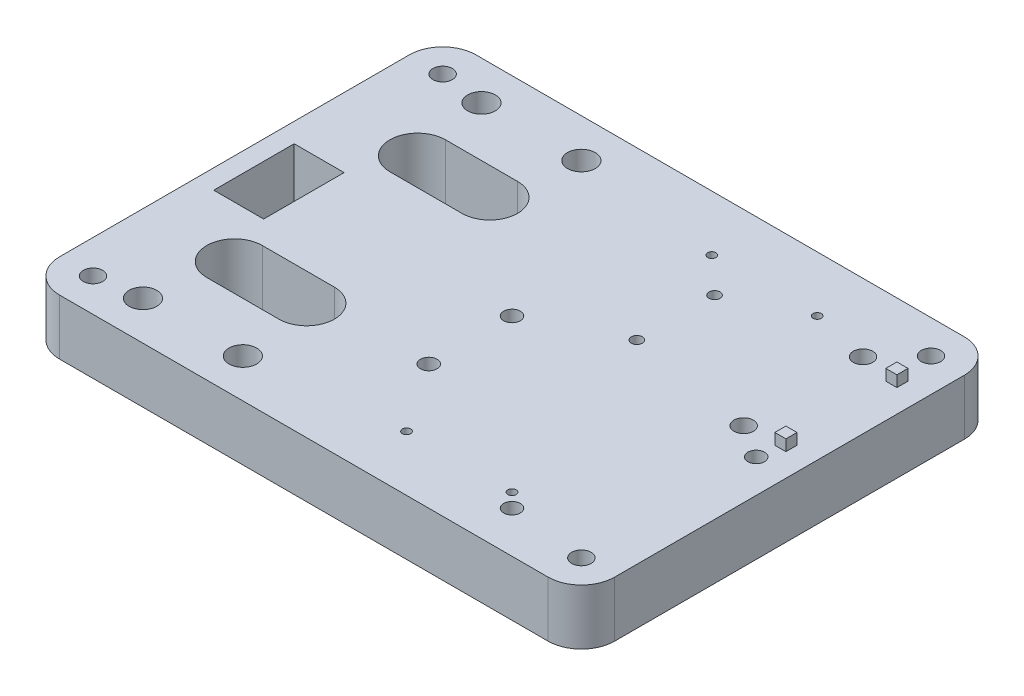
SolidWorks part; units mm, degrees
ref_plane "Спереди" through (0, 0, 0) normal (0, 0, 1) x (1, 0, 0)
ref_plane "Сверху" through (0, 0, 0) normal (0, 1, 0) x (1, 0, 0)
ref_plane "Справа" through (0, 0, 0) normal (1, 0, 0) x (0, 0, -1)
sketch "Эскиз1" plane through (0, 0, 0) normal (0, 1, 0) x (1, 0, 0)
  line L0 (0, 37.5) -> (100, 37.5) construction
  line L17 (0, 0) -> (100, 0)
  line L18 (0, 0) -> (0, 75)
  line L19 (0, 75) -> (100, 75)
  line L20 (100, 0) -> (100, 75)
  line L21 (50, 75) -> (50, 0) construction
  line L22 (23, 75) -> (23, 0) construction
  line L25 (16.5, 54) -> (29.5, 54) construction
  line L26 (16.5, 59) -> (29.5, 59)
  line L27 (16.5, 49) -> (29.5, 49)
  line L28 (16.5, 21) -> (29.5, 21) construction
  line L29 (16.5, 16) -> (29.5, 16)
  line L30 (16.5, 26) -> (29.5, 26)
  line L31 (68, 75) -> (68, 0) construction
  line L33 (3.5, 44.75) -> (12.5, 44.75)
  line L34 (3.5, 44.75) -> (3.5, 30.25)
  line L35 (3.5, 30.25) -> (12.5, 30.25)
  line L36 (12.5, 44.75) -> (12.5, 30.25)
  line L37 (3.5, 44.75) -> (12.5, 30.25) construction
  line L38 (3.5, 30.25) -> (12.5, 44.75) construction
  circle A8 centre (6, 69) radius 1.75
  circle A9 centre (94, 69) radius 1.75
  circle A10 centre (94, 6) radius 1.75
  circle A11 centre (6, 6) radius 1.75
  circle A16 centre (14, 68) radius 1.25
  circle A17 centre (32, 68) radius 1.25
  arc A18 (16.5, 59) -> (16.5, 49) centre (16.5, 54) ccw
  arc A19 (29.5, 49) -> (29.5, 59) centre (29.5, 54) ccw
  arc A20 (16.5, 16) -> (16.5, 26) centre (16.5, 21) cw
  arc A21 (29.5, 26) -> (29.5, 16) centre (29.5, 21) cw
  circle A22 centre (32, 7) radius 1.25
  circle A23 centre (14, 7) radius 1.25
  circle A24 centre (58.5, 65) radius 0.75
  circle A25 centre (77.5, 65) radius 0.75
  circle A26 centre (77.5, 10) radius 0.75
  circle A27 centre (58.5, 10) radius 0.75
  circle A28 centre (94, 37.5) radius 1.5
  point P13 (23, 54)
  point P23 (23, 21)
  point P51 (8, 37.5)
  dimension "D3" = 18
  dimension "D8" = 21
  dimension "D9" = 2.5
  dimension "D10" = 1.5
  dimension "D12" = 55
  dimension "D15" = 3.5
  dimension "D4" = 23
  dimension "D11" = 19
  dimension "D20" = 3
  dimension "D1" = 75
  dimension "D2" = 100
  dimension "D5" = 7
  dimension "D6" = 10
  dimension "D7" = 13
  dimension "D13" = 6
  dimension "D14" = 6
  dimension "D16" = 32
  dimension "D17" = 9
  dimension "D18" = 14.5
  dimension "D19" = 8
  dimension "D21" = 6
extrude "Бобышка-Вытянуть1" add sketch "Эскиз1" along normal blind 10
fillet "Скругление5" radius 6 4 edges at (100, 5, 0) (100, 5, -75) (0, 5, 0) (0, 5, -75)
sketch "Эскиз2" plane through (0, 0, 0) normal (0, -1, 0) x (1, 0, 0)
  line L1 (100, -6) -> (100, -69) construction
  line L2 (100, -52) -> (4.002, -52) construction
  line L3 (94, -75) -> (6, -75) construction
  circle A3 centre (80, -7.5) radius 1.5
  circle A31 centre (50, -37.5) radius 1.5
  circle A35 centre (88, -62.75) radius 1.75
  circle A36 centre (88, -41.25) radius 1.75
  circle A68 centre (50, -22.5) radius 1.5
  circle A70 centre (50, -7.5) radius 1.5 [skipped]
  circle A71 centre (80, -22.5) radius 1.5 [skipped]
  circle A72 centre (65, -59) radius 1
  circle A73 centre (65, -45) radius 1
  dimension "D1" = 2
  dimension "D5" = 2
  dimension "D7" = 3.5
  dimension "D4" = 35
  dimension "D3" = 14
  dimension "D6" = 23
  dimension "D8" = 21.5
  dimension "D9" = 12
  dimension "D2" = 2
extrude "Вырез-Вытянуть1" cut sketch "Эскиз2" against normal up to next
sketch "Эскиз3" plane through (0, 10, 0) normal (0, 1, 0) x (1, 0, 0)
  circle A0 centre (14, 68) radius 2.5
  circle A1 centre (32, 68) radius 2.5
  circle A2 centre (14, 7) radius 2.5
  circle A3 centre (32, 7) radius 2.5
  dimension "D1" = 5
extrude "Вырез-Вытянуть2" cut sketch "Эскиз3" against normal blind 7
sketch "Эскиз4" plane through (0, 10, 0) normal (0, 1, 0) x (1, 0, 0)
  line L0 (100, 52) -> (0, 52) construction
  line L1 (100, 6) -> (100, 69) construction
  line L2 (0, 69) -> (0, 6) construction
  line L3 (94, 75) -> (6, 75) construction
  line L5 (93.8557, 43) -> (95.8557, 43)
  line L6 (93.8557, 43) -> (93.8557, 41)
  line L7 (93.8557, 41) -> (95.8557, 41)
  line L8 (95.8557, 43) -> (95.8557, 41)
  line L9 (93.8557, 63) -> (95.8557, 63)
  line L10 (93.8557, 63) -> (93.8557, 61)
  line L11 (93.8557, 61) -> (95.8557, 61)
  line L12 (95.8557, 63) -> (95.8557, 61)
  dimension "D1" = 23
  dimension "D2" = 2
  dimension "D3" = 18
extrude "Бобышка-Вытянуть2" add sketch "Эскиз4" along normal blind 2
